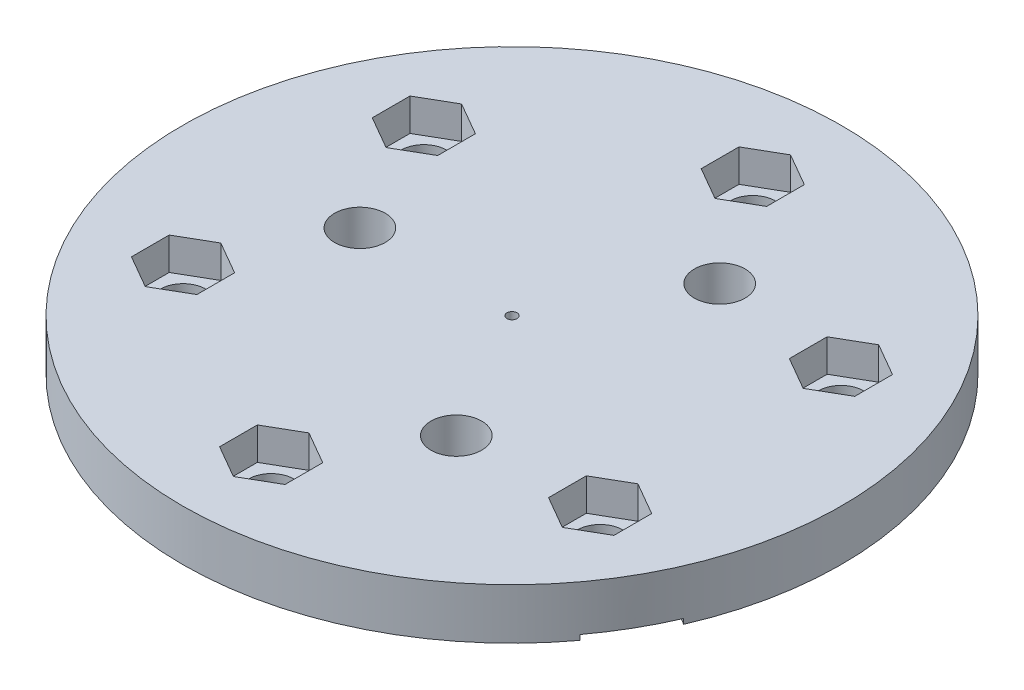
SolidWorks part; units mm, degrees
ref_plane "Front Plane" through (0, 0, 0) normal (0, 0, 1) x (1, 0, 0)
ref_plane "Top Plane" through (0, 0, 0) normal (0, 1, 0) x (1, 0, 0)
ref_plane "Right Plane" through (0, 0, 0) normal (1, 0, 0) x (0, 0, -1)
sketch "Sketch1" plane through (0, 0, 0) normal (0, 1, 0) x (1, 0, 0)
  circle A0 centre (0, 0) radius 65
  circle A1 centre (0, 0) radius 1
  dimension "D1" = 130
  dimension "D2" = 2
extrude "Boss-Extrude1" add sketch "Sketch1" along normal mid plane 10
sketch "Sketch3" plane through (0, 5, 0) normal (0, 1, 0) x (1, 0, 0)
  line L0 (0, 65) -> (0, -65) construction
  line L1 (-65, 0) -> (65, 0) construction
  line L2 (34.6862, 20.0261) -> (41.1362, 16.3022)
  line L3 (0, 40.0522) -> (6.45, 43.7761)
  line L4 (6.45, 43.7761) -> (6.45, 51.2239)
  line L5 (6.45, 51.2239) -> (0, 54.9478)
  line L6 (0, 54.9478) -> (-6.45, 51.2239)
  line L7 (-6.45, 51.2239) -> (-6.45, 43.7761)
  line L8 (-6.45, 43.7761) -> (0, 40.0522)
  line L9 (41.1362, 16.3022) -> (47.5862, 20.0261)
  line L10 (47.5862, 20.0261) -> (47.5862, 27.4739)
  line L11 (47.5862, 27.4739) -> (41.1362, 31.1978)
  line L12 (41.1362, 31.1978) -> (34.6862, 27.4739)
  line L13 (34.6862, 27.4739) -> (34.6862, 20.0261)
  line L14 (34.6862, -20.0261) -> (34.6862, -27.4739)
  line L15 (34.6862, -27.4739) -> (41.1362, -31.1978)
  line L16 (41.1362, -31.1978) -> (47.5862, -27.4739)
  line L17 (47.5862, -27.4739) -> (47.5862, -20.0261)
  line L18 (47.5862, -20.0261) -> (41.1362, -16.3022)
  line L19 (41.1362, -16.3022) -> (34.6862, -20.0261)
  line L20 (0, -40.0522) -> (-6.45, -43.7761)
  line L21 (-6.45, -43.7761) -> (-6.45, -51.2239)
  line L22 (-6.45, -51.2239) -> (0, -54.9478)
  line L23 (0, -54.9478) -> (6.45, -51.2239)
  line L24 (6.45, -51.2239) -> (6.45, -43.7761)
  line L25 (6.45, -43.7761) -> (0, -40.0522)
  line L26 (-34.6862, -20.0261) -> (-41.1362, -16.3022)
  line L27 (-41.1362, -16.3022) -> (-47.5862, -20.0261)
  line L28 (-47.5862, -20.0261) -> (-47.5862, -27.4739)
  line L29 (-47.5862, -27.4739) -> (-41.1362, -31.1978)
  line L30 (-41.1362, -31.1978) -> (-34.6862, -27.4739)
  line L31 (-34.6862, -27.4739) -> (-34.6862, -20.0261)
  line L32 (-34.6862, 20.0261) -> (-34.6862, 27.4739)
  line L33 (-34.6862, 27.4739) -> (-41.1362, 31.1978)
  line L34 (-41.1362, 31.1978) -> (-47.5862, 27.4739)
  line L35 (-47.5862, 27.4739) -> (-47.5862, 20.0261)
  line L36 (-47.5862, 20.0261) -> (-41.1362, 16.3022)
  line L37 (-41.1362, 16.3022) -> (-34.6862, 20.0261)
  circle A0 centre (0, 0) radius 65 construction
  circle A2 centre (0, 47.5) radius 6.45 construction
  point P48 (0, 0)
  dimension "D1" = 12.9
  dimension "D2" = 47.5
  dimension "D3" = 6
extrude "Cut-Extrude1" cut sketch "Sketch3" against normal blind 6.4
sketch "Sketch4" plane through (0, -1.4, 0) normal (0, 1, 0) x (1, 0, 0)
  line L0 (0, 47.5) -> (0, 0) construction
  circle A0 centre (0, 47.5) radius 4.5
  circle A11 centre (0, 47.5) radius 4.5 construction
  circle A12 centre (41.1362, 23.75) radius 4.5
  circle A13 centre (41.1362, -23.75) radius 4.5
  circle A14 centre (0, -47.5) radius 4.5
  circle A15 centre (-41.1362, -23.75) radius 4.5
  circle A16 centre (-41.1362, 23.75) radius 4.5
  point P12 (0, 47.5)
  point P21 (0, 0)
  point P23 (6.4952, 3.75)
  point P24 (-2.1651, -1.25)
  dimension "D1" = 9
  dimension "D3" = 47.5
  dimension "D2" = 6
extrude "Cut-Extrude2" cut sketch "Sketch4" against normal through all
sketch "Sketch5" plane through (0, 5, 0) normal (0, 1, 0) x (1, 0, 0)
  line L0 (0, 72.6384) -> (0, 0) construction
  line L3 (60.4635, -26.2484) -> (7.5, 4.3301)
  line L4 (7.5, 65.4872) -> (-7.5, 65.4872)
  line L5 (7.5, 65.4872) -> (7.5, 4.3301)
  line L7 (-7.5, 65.4872) -> (-7.5, 4.3301)
  line L8 (7.5, 65.4872) -> (0, 32.7436) construction
  line L10 (52.9635, -39.2388) -> (0, -8.6603)
  line L11 (52.9635, -39.2388) -> (60.4635, -26.2484)
  line L13 (-52.9635, -39.2388) -> (0, -8.6603)
  line L14 (-60.4635, -26.2484) -> (-7.5, 4.3301)
  line L15 (-60.4635, -26.2484) -> (-52.9635, -39.2388)
  line L18 (0, 32.7436) -> (-7.5, 65.4872) construction
  point P1 (0, 32.7436)
  point P6 (7.5, 4.3301)
  point P20 (0, 0)
  dimension "D3" = 3
extrude "Cut-Extrude3" cut sketch "Sketch5" against normal blind 3 from offset 9 offset against normal yes
sketch "Sketch6" plane through (0, -5, 0) normal (0, -1, 0) x (1, 0, 0)
  line L0 (0, 0) -> (-56.2917, 32.5) construction
  line L1 (0, 0) -> (0, -65) construction
  circle A0 centre (-30, 0) radius 5
  arc A1 (-52.1657, 38.7781) -> (-59.6657, 25.7877) centre (0, 0) ccw construction
  arc A2 (-7.5, -64.5659) -> (7.5, -64.5659) centre (0, 0) ccw construction
  circle A3 centre (15, 25.9808) radius 5
  circle A4 centre (15, -25.9808) radius 5
  point P18 (0, 0)
  dimension "D1" = 10
  dimension "D2" = 15
  dimension "D3" = 30
  dimension "D4" = 3
extrude "Cut-Extrude4" cut sketch "Sketch6" against normal through all
